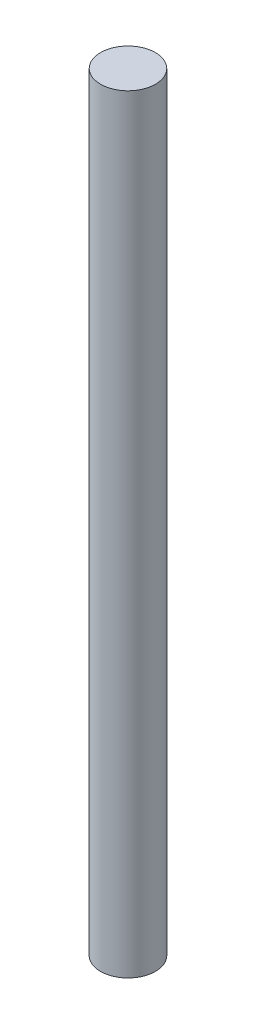
SolidWorks part; units mm, degrees
material "Beech"
ref_plane "Front Plane" through (0, 0, 0) normal (0, 0, 1) x (1, 0, 0)
ref_plane "Top Plane" through (0, 0, 0) normal (0, 1, 0) x (1, 0, 0)
ref_plane "Right Plane" through (0, 0, 0) normal (1, 0, 0) x (0, 0, -1)
sketch "Sketch1" plane through (0, 0, 0) normal (0, 1, 0) x (1, 0, 0)
  circle A0 centre (0, 0) radius 3.175
extrude "Extrude1" add sketch "Sketch1" along normal blind 88.9
